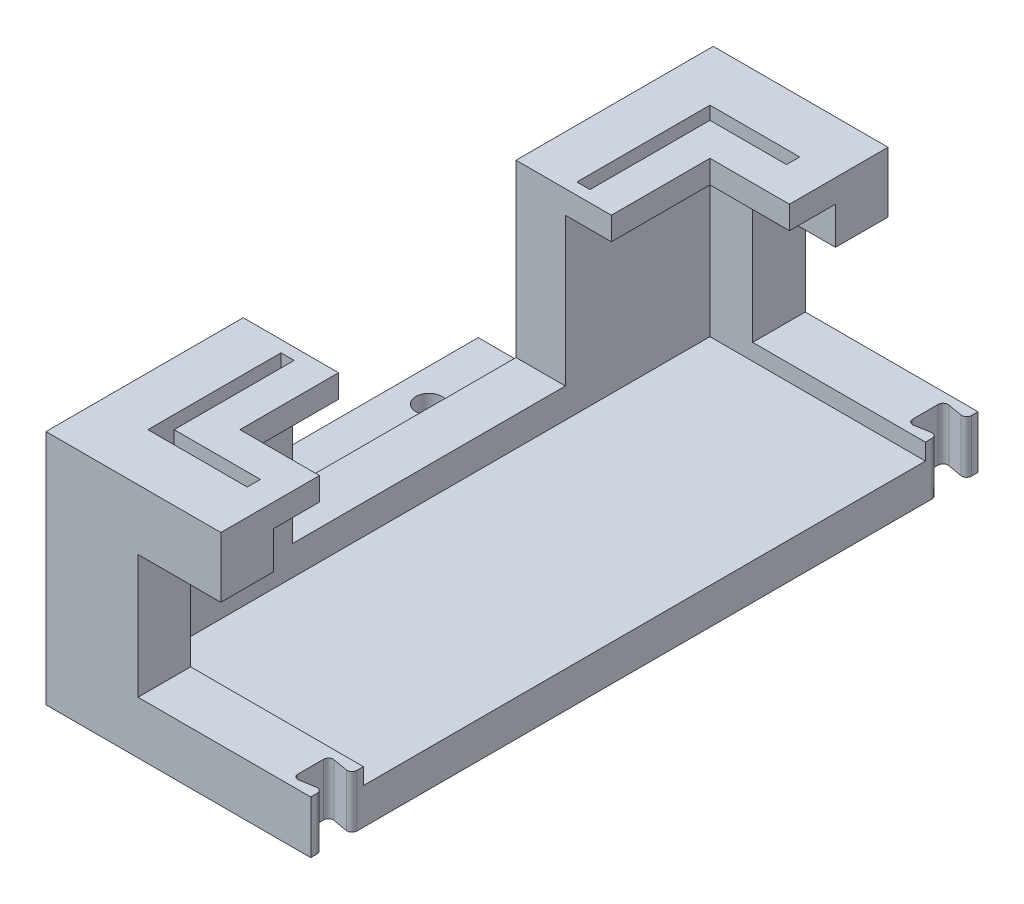
SolidWorks part; units mm, degrees
ref_plane "Front Plane" through (0, 0, 0) normal (0, 0, 1) x (1, 0, 0)
ref_plane "Top Plane" through (0, 0, 0) normal (0, 1, 0) x (1, 0, 0)
ref_plane "Right Plane" through (0, 0, 0) normal (1, 0, 0) x (0, 0, -1)
sketch "Sketch1" plane through (0, 0, 0) normal (0, 1, 0) x (1, 0, 0)
  line L1 (-184.5, -101.5) -> (184.5, -101.5)
  line L2 (-184.5, -101.5) -> (-184.5, 101.5)
  line L3 (-184.5, 101.5) -> (184.5, 101.5)
  line L4 (184.5, -101.5) -> (184.5, 101.5)
  line L5 (-184.5, -101.5) -> (184.5, 101.5) construction
  line L6 (-184.5, 101.5) -> (184.5, -101.5) construction
  point P0 (0, 0)
  dimension "D1" = 203
  dimension "353" = 369
extrude "Boss-Extrude1" add sketch "Sketch1" along normal blind 20
sketch "Sketch2" plane through (0, 20, 0) normal (0, 1, 0) x (1, 0, 0)
  line L0 (-184.5, -101.5) -> (184.5, -101.5) construction
  line L1 (-184.5, -101.5) -> (-169.5, -101.5)
  line L2 (-184.5, -101.5) -> (-184.5, -36.5)
  line L3 (-184.5, -36.5) -> (-169.5, -36.5)
  line L4 (-169.5, -85.5) -> (-169.5, -36.5)
  line L5 (-184.5, 101.5) -> (-169.5, 101.5)
  line L6 (-184.5, 101.5) -> (-184.5, 36.5)
  line L7 (-184.5, 36.5) -> (-169.5, 36.5)
  line L8 (-169.5, 85.5) -> (-169.5, 36.5)
  line L9 (-169.5, 101.5) -> (-119.5, 101.5)
  line L11 (-169.5, 85.5) -> (-119.5, 85.5)
  line L12 (-119.5, 101.5) -> (-119.5, 85.5)
  line L13 (-169.5, -101.5) -> (-119.5, -101.5)
  line L15 (-169.5, -85.5) -> (-119.5, -85.5)
  line L16 (-119.5, -101.5) -> (-119.5, -85.5)
  line L17 (-44.5, -101.5) -> (84.5, -101.5)
  line L18 (-44.5, -101.5) -> (-44.5, -85.5)
  line L19 (-44.5, -85.5) -> (84.5, -85.5)
  line L20 (84.5, -101.5) -> (84.5, -85.5)
  line L21 (184.5, 101.5) -> (-184.5, 101.5) construction
  line L22 (-44.5, 101.5) -> (84.5, 101.5)
  line L23 (-44.5, 101.5) -> (-44.5, 85.5)
  line L24 (-44.5, 85.5) -> (84.5, 85.5)
  line L25 (84.5, 101.5) -> (84.5, 85.5)
  line L26 (184.5, -101.5) -> (184.5, 101.5) construction
  point P28 (84.5, -93.5)
  point P31 (0, 0)
  dimension "D1" = 65
  dimension "D2" = 15
  dimension "D3" = 65
  dimension "D4" = 15
  dimension "D5" = 16
  dimension "D6" = 50
  dimension "D7" = 50
  dimension "D8" = 16
  dimension "D9" = 75
  dimension "D10" = 100
extrude "Boss-Extrude2" add sketch "Sketch2" along normal blind 12
sketch "Sketch3" plane through (0, 20, 0) normal (0, 1, 0) x (1, 0, 0)
  line L0 (-119.5, -85.5) -> (-169.5, -85.5) construction
  line L1 (-169.5, 85.5) -> (172.5, 85.5)
  line L2 (-169.5, 85.5) -> (-169.5, -85.5)
  line L3 (-169.5, -85.5) -> (172.5, -85.5)
  line L4 (172.5, 85.5) -> (172.5, -85.5)
  dimension "D1" = 342
extrude "Cut-Extrude1" cut sketch "Sketch3" against normal blind 9
sketch "Sketch4" plane through (0, 0, -101.5) normal (0, 0, -1) x (-1, 0, 0)
  line L0 (-84.5, 32) -> (44.5, 32) construction
  line L1 (-69.5, 20) -> (30.5, 20)
  line L2 (-69.5, 20) -> (-69.5, 32)
  line L3 (-69.5, 32) -> (30.5, 32)
  line L4 (30.5, 20) -> (30.5, 32)
  line L5 (-69.5, 20) -> (30.5, 32) construction
  line L6 (-69.5, 32) -> (30.5, 20) construction
  line L8 (-84.5, 32) -> (-84.5, 20) construction
  point P0 (-19.5, 26)
  dimension "D1" = 100
  dimension "D2" = 15
extrude "Boss-Extrude3" add sketch "Sketch4" along normal blind 60
sketch "Sketch6" plane through (0, 0, -85.5) normal (0, 0, 1) x (1, 0, 0)
  line L0 (-24.5, 32) -> (-26.7871, 29.1015)
  line L1 (-44.5, 32) -> (84.5, 32) construction
  line L2 (-25.3663, 26.1706) -> (-15.6337, 26.1706)
  line L3 (-14.2129, 29.1015) -> (-16.5, 32)
  line L4 (-16.5, 32) -> (-24.5, 32)
  line L5 (-44.5, 32) -> (84.5, 32) construction
  line L6 (-44.5, 32) -> (-44.5, 20) construction
  line L7 (56.5, 32) -> (54.2501, 28.6971)
  line L8 (55.6337, 26.0806) -> (65.3663, 26.0806)
  line L9 (66.7499, 28.6971) -> (64.5, 32)
  line L10 (64.5, 32) -> (56.5, 32)
  line L12 (84.5, 32) -> (84.5, 20) construction
  arc A0 (-26.7871, 29.1015) -> (-25.3663, 26.1706) centre (-25.3663, 27.9804) ccw
  arc A1 (-15.6337, 26.1706) -> (-14.2129, 29.1015) centre (-15.6337, 27.9804) ccw
  arc A2 (54.2501, 28.6971) -> (55.6337, 26.0806) centre (55.6337, 27.7546) ccw
  arc A3 (65.3663, 26.0806) -> (66.7499, 28.6971) centre (65.3663, 27.7546) ccw
  dimension "D1" = 8
  dimension "D2" = 20
  dimension "D3" = 8
  dimension "D4" = 20
extrude "Cut-Extrude3" cut sketch "Sketch6" against normal blind 60 and the other way blind 10
sketch "Sketch8" plane through (0, 32, 0) normal (0, 1, 0) x (1, 0, 0)
  line L0 (-184.5, 36.5) -> (-169.5, 36.5)
  line L1 (-169.5, 36.5) -> (-169.5, 85.5)
  line L2 (-169.5, 85.5) -> (-119.5, 85.5)
  line L3 (-119.5, 85.5) -> (-119.5, 101.5)
  line L4 (-119.5, 101.5) -> (-184.5, 101.5)
  line L5 (-184.5, 101.5) -> (-184.5, 36.5)
extrude "Boss-Extrude5" add sketch "Sketch8" along normal blind 40
sketch "Sketch9" plane through (0, 72, 0) normal (0, 1, 0) x (1, 0, 0)
  line L0 (-119.5, 85.5) -> (-119.5, 71.5)
  line L1 (-119.5, 71.5) -> (-155.5, 71.5)
  line L2 (-155.5, 71.5) -> (-155.5, 35)
  line L3 (-155.5, 35) -> (-169.5, 35)
  line L4 (-169.5, 36.5) -> (-169.5, 85.5) construction
  line L5 (-169.5, 85.5) -> (-169.5, -85.5) construction
  line L6 (172.5, 85.5) -> (-169.5, 85.5) construction
  dimension "D1" = 14
  dimension "D2" = 14
extrude "Extrude-Thin1" add sketch "Sketch9" against normal blind 7 thin
mirror "Mirror2" about plane through (0, 0, 0) normal (0, 0, 1) of "Boss-Extrude5", "Boss-Extrude3", "Cut-Extrude3", "Extrude-Thin1"
sketch "Sketch10" plane through (0, 32, 0) normal (0, 1, 0) x (1, 0, 0)
  line L1 (-103.95, 161.5046) -> (300.05, 161.5046)
  line L2 (-103.95, 161.5046) -> (-103.95, -163.2916)
  line L3 (-103.95, -163.2916) -> (300.05, -163.2916)
  line L4 (300.05, 161.5046) -> (300.05, -163.2916)
  line L6 (-184.5, 36.5) -> (-184.5, -36.5) construction
  dimension "D1" = 80.55
  dimension "D2" = 404
extrude "Cut-Extrude4" cut sketch "Sketch10" against normal blind 69
sketch "Sketch14" plane through (0, 0, -101.5) normal (0, 0, -1) x (-1, 0, 0)
  line L5 (119.5, 72) -> (119.5, 20) construction
  line L6 (119.5, 53.6124) -> (156.5, 53.6124)
  line L7 (119.5, 53.6124) -> (119.5, 18.895)
  line L8 (119.5, 18.895) -> (156.5, 18.895)
  line L9 (156.5, 53.6124) -> (156.5, 18.895)
  line L10 (184.5, 72) -> (184.5, 0) construction
  dimension "D1" = 28
extrude "Cut-Extrude7" cut sketch "Sketch14" against normal through all both and the other way through all
sketch "Sketch11" plane through (0, 20, 0) normal (0, 1, 0) x (1, 0, 0)
  line L2 (-103.95, 97.75) -> (-103.95, 89.25)
  line L5 (-103.95, 97.75) -> (-111.95, 99.1606)
  line L6 (-111.95, 99.1606) -> (-111.95, 87.8394)
  line L7 (-111.95, 87.8394) -> (-103.95, 89.25)
  line L8 (-103.95, -85.5) -> (-103.95, -101.5) construction
  line L9 (-103.95, 101.5) -> (-119.5, 101.5) construction
  line L11 (-103.95, -89.25) -> (-103.95, -97.75)
  line L15 (-103.95, 85.5) -> (-103.95, 101.5) construction
  line L18 (-103.95, -89.25) -> (-111.95, -87.8394)
  line L19 (-111.95, -87.8394) -> (-111.95, -99.1606)
  line L20 (-111.95, -99.1606) -> (-103.95, -97.75)
  line L21 (-103.95, -101.5) -> (-103.95, -85.5) construction
  line L22 (-119.5, -101.5) -> (-103.95, -101.5) construction
  dimension "D2" = 3.75
  dimension "D3" = 80
  dimension "D4" = 80
  dimension "D5" = 80
  dimension "D6" = 3.75
  dimension "D7" = 3.75
  dimension "D8" = 80
  dimension "D9" = 3.75
  dimension "D10" = 8
  dimension "D11" = 8
sketch "Sketch12" plane through (-184.5, 0, 0) normal (-1, 0, 0) x (0, 0, 1)
  line L1 (0, 0) -> (-50, 0)
  line L2 (0, 0) -> (0, 11)
  line L3 (0, 11) -> (-50, 11)
  line L4 (-50, 0) -> (-50, 11)
  dimension "D1" = 11
  dimension "D2" = 50
extrude "Boss-Extrude6" add sketch "Sketch12" along normal blind 20
sketch "Sketch13" plane through (0, 11, 0) normal (0, 1, 0) x (1, 0, 0)
  line L0 (-204.5, 0) -> (-204.5, 50) construction
  line L1 (-204.5, 50) -> (-184.5, 50) construction
  circle A0 centre (-194.5, 25) radius 4
  dimension "D1" = 10
  dimension "D2" = 25
extrude "Cut-Extrude6" cut sketch "Sketch13" against normal through all
mirror "Mirror3" about plane through (0, 0, 0) normal (0, 0, 1) of "Cut-Extrude6", "Boss-Extrude6"
extrude "Cut-Extrude9" cut sketch "Sketch11" against normal through all
sketch "Sketch16" plane through (0, 0, 101.5) normal (0, 0, 1) x (1, 0, 0)
  line L0 (-156.5, 53.6124) -> (-119.5, 53.6124) construction
  line L1 (-119.5, 72) -> (-131.3145, 72)
  line L2 (-119.5, 72) -> (-119.5, 53.6124)
  line L3 (-119.5, 53.6124) -> (-131.3145, 53.6124)
  line L4 (-131.3145, 72) -> (-131.3145, 53.6124)
extrude "Cut-Extrude10" cut sketch "Sketch16" against normal through all
sketch "Sketch18" plane through (0, 72, 0) normal (0, 1, 0) x (1, 0, 0)
  line L1 (-131.3145, -71.5) -> (-139.2597, -71.5)
  line L2 (-131.3145, -71.5) -> (-131.3145, -92.041)
  line L3 (-131.3145, -92.041) -> (-139.2597, -92.041)
  line L4 (-139.2597, -71.5) -> (-139.2597, -92.041)
extrude "Boss-Extrude8" add sketch "Sketch18" against normal up to vertex
sketch "Sketch19" plane through (0, 72, 0) normal (0, 1, 0) x (1, 0, 0)
  line L1 (-131.3145, 71.5) -> (-142.1923, 71.5)
  line L2 (-131.3145, 71.5) -> (-131.3145, 90.9542)
  line L3 (-131.3145, 90.9542) -> (-142.1923, 90.9542)
  line L4 (-142.1923, 71.5) -> (-142.1923, 90.9542)
extrude "Boss-Extrude9" add sketch "Sketch19" against normal up to vertex
fillet "Fillet1" radius 1.5 8 edges at (-111.95, 10, -99.1606) (-103.95, 10, -97.75) (-103.95, 10, -89.25) (-111.95, 10, -87.8394) (-103.95, 10, 97.75) (-111.95, 10, 99.1606) (-111.95, 10, 87.8394) (-103.95, 10, 89.25)
sketch "Sketch20" plane through (0, 0, 101.5) normal (0, 0, 1) x (1, 0, 0)
  line L0 (-156.5, 18.895) -> (-156.5, 53.6124) construction
  line L1 (-146.5, 18.895) -> (-156.5, 18.895)
  line L2 (-146.5, 18.895) -> (-146.5, 15.995)
  line L3 (-146.5, 15.995) -> (-156.5, 15.995)
  line L4 (-156.5, 18.895) -> (-156.5, 15.995)
  point P7 (0, 0)
  point P8 (0, 0)
  dimension "D1" = 2.9
extrude "Cut-Extrude11" cut sketch "Sketch20" against normal through all both and the other way through all
sketch "Sketch21" plane through (-184.5, 0, 0) normal (-1, 0, 0) x (0, 0, 1)
  line L0 (-101.5, 72) -> (-36.5, 72) construction
  line L1 (-41.5, 72) -> (-33.1471, 72)
  line L2 (-41.5, 72) -> (-41.5, 20)
  line L3 (-41.5, 20) -> (-33.1471, 20)
  line L4 (-33.1471, 72) -> (-33.1471, 20)
  line L5 (-36.5, 20) -> (36.5, 20) construction
  line L6 (-101.5, 72) -> (-101.5, 0) construction
  line L7 (35, 72) -> (41.5, 72)
  line L8 (35, 72) -> (35, 20)
  line L9 (35, 20) -> (41.5, 20)
  line L10 (41.5, 72) -> (41.5, 20)
  line L11 (101.5, 72) -> (101.5, 0) construction
  dimension "D1" = 60
  dimension "D2" = 60
extrude "Cut-Extrude12" cut sketch "Sketch21" against normal through all
sketch "Sketch22" plane through (0, 0, 101.5) normal (0, 0, 1) x (1, 0, 0)
  line L1 (-146.5, 15.995) -> (-103.3169, 15.995)
  line L2 (-146.5, 15.995) -> (-146.5, 28.4244)
  line L3 (-146.5, 28.4244) -> (-103.3169, 28.4244)
  line L4 (-103.3169, 15.995) -> (-103.3169, 28.4244)
extrude "Cut-Extrude13" cut sketch "Sketch22" against normal through all
